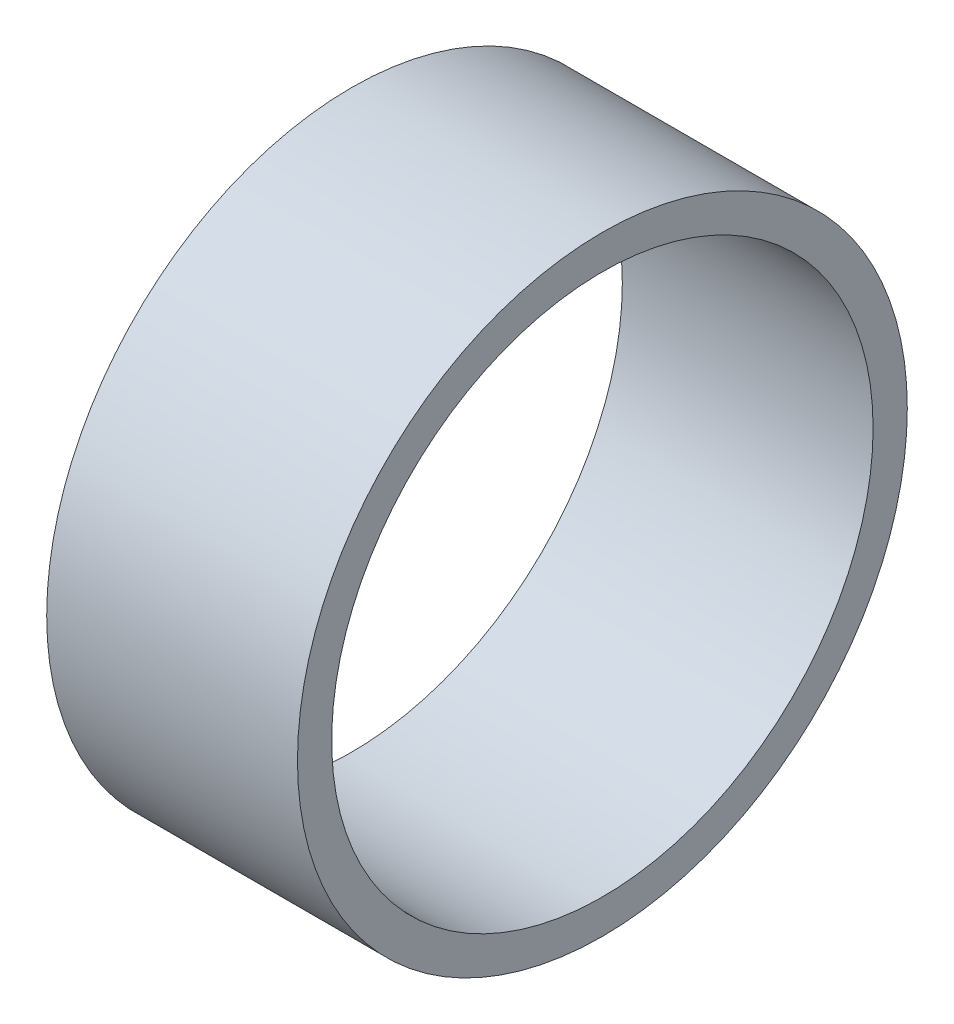
SolidWorks part; units mm, degrees
ref_plane "前视基准面" through (0, 0, 0) normal (0, 0, 1) x (1, 0, 0)
ref_plane "上视基准面" through (0, 0, 0) normal (0, 1, 0) x (1, 0, 0)
ref_plane "右视基准面" through (0, 0, 0) normal (1, 0, 0) x (0, 0, -1)
sketch "草图2" plane through (0, 0, 0) normal (1, 0, 0) x (0, 0, -1)
  circle A0 centre (0, 0) radius 53.5
  circle A1 centre (0, 0) radius 47.5
  dimension "D1" = 107
  dimension "D2" = 95
extrude "凸台-拉伸1" add sketch "草图2" along normal blind 44
